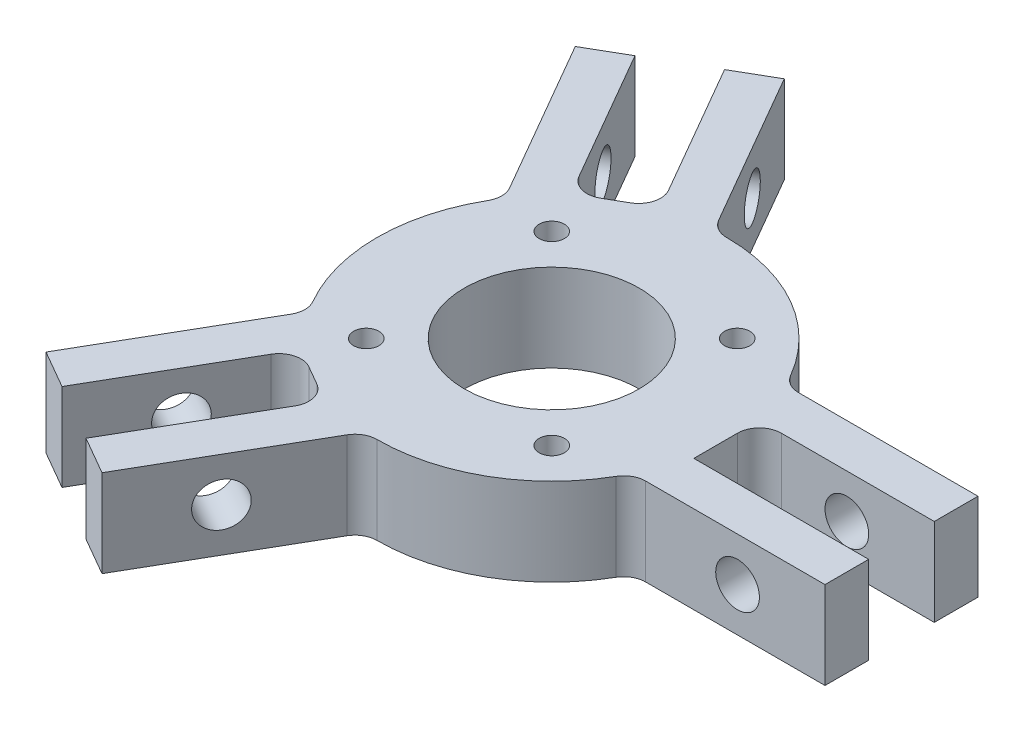
SolidWorks part; units mm, degrees
material "6061 Alloy"
ref_plane "Front Plane" through (0, 0, 0) normal (0, 0, 1) x (1, 0, 0)
ref_plane "Top Plane" through (0, 0, 0) normal (0, 1, 0) x (1, 0, 0)
ref_plane "Right Plane" through (0, 0, 0) normal (1, 0, 0) x (0, 0, -1)
sketch3d "Planning"
  line L0 (0, 0, 0) -> (38.1, 0, 0) construction
  line L1 (38.1, 0, 0) -> (355.6, -190.5, 0) construction
  line L2 (355.6, -190.5, 0) -> (355.6, -203.2, 0) construction
  line L3 (0, 0, 0) -> (-19.05, 0, 32.9956) construction
  line L4 (0, 0, 0) -> (-19.05, 0, -32.9956) construction
  line L5 (-19.05, 0, 32.9956) -> (-127, -190.5, 219.9705) construction
  line L6 (-127, -190.5, 219.9705) -> (-127, -203.2, 219.9705) construction
  line L7 (-19.05, 0, -32.9956) -> (-127, -190.5, -219.9705) construction
  line L8 (-127, -190.5, -219.9705) -> (-127, -203.2, -219.9705) construction
  line L9 (-19.05, 0, -32.9956) -> (-19.05, 0, 32.9956) construction
  line L10 (-127, -203.2, -219.9705) -> (-127, -203.2, 219.9705) construction
  line L11 (355.6, -203.2, 0) -> (-127, -203.2, 0) construction
  line L12 (0, 0, 0) -> (0, -203.2, 0) construction
  point P11 (-19.05, 0, 0)
  dimension "D1" = 38.1
  dimension "D2" = 12.7
  dimension "D3" = 203.2
  dimension "D4" = 482.6
  dimension "D5" = 127
  dimension "D6" = 120
sketch "Sketch1" plane through (0, 0, 0) normal (0, 1, 0) x (1, 0, 0)
  line L0 (0, 0) -> (25.4, 0) construction
  line L1 (25.4, 4.7625) -> (25.4, -4.7625)
  line L2 (25.4, -4.7625) -> (50.8, -4.7625)
  line L3 (50.8, -4.7625) -> (50.8, -11.1125)
  line L4 (25.4, 4.7625) -> (50.8, 4.7625)
  line L5 (13.4704, 13.4704) -> (-13.4704, -13.4704) construction
  line L6 (13.4704, -13.4704) -> (-13.4704, 13.4704) construction
  line L7 (50.8, 4.7625) -> (50.8, 11.1125)
  line L8 (0, 0) -> (-12.7, -21.997) construction
  line L9 (38.1, 4.7625) -> (38.1, -4.7625) construction
  line L10 (-35.0237, -38.4378) -> (-29.5244, -41.6128)
  line L11 (-29.5244, -41.6128) -> (-16.8244, -19.6158)
  line L12 (-16.8244, -19.6158) -> (-8.5756, -24.3783)
  line L13 (-8.5756, -24.3783) -> (-21.2756, -46.3753)
  line L14 (-21.2756, -46.3753) -> (-15.7763, -49.5503)
  line L15 (-15.7763, -49.5503) -> (-1.7964, -25.3364)
  line L16 (50.8, -11.1125) -> (22.8401, -11.1125)
  line L17 (-35.0237, -38.4378) -> (-21.0438, -14.2239)
  line L18 (0, 0) -> (-12.7, 21.997) construction
  line L19 (-15.7763, 49.5503) -> (-1.7964, 25.3364)
  line L20 (-21.2756, 46.3753) -> (-15.7763, 49.5503)
  line L21 (-8.5756, 24.3783) -> (-21.2756, 46.3753)
  line L22 (-16.8244, 19.6158) -> (-8.5756, 24.3783)
  line L23 (-29.5244, 41.6128) -> (-16.8244, 19.6158)
  line L24 (-35.0237, 38.4378) -> (-29.5244, 41.6128)
  line L25 (-35.0237, 38.4378) -> (-21.0438, 14.2239)
  line L26 (50.8, 11.1125) -> (22.8401, 11.1125)
  line L27 (0, 0) -> (-19.05, 32.9956) construction
  circle A0 centre (0, 0) radius 12.7
  circle A1 centre (-13.4704, 13.4704) radius 1.8288
  circle A2 centre (13.4704, 13.4704) radius 1.8288
  circle A3 centre (13.4704, -13.4704) radius 1.8288
  circle A4 centre (-13.4704, -13.4704) radius 1.8288
  arc A5 (-1.7964, -25.3364) -> (22.8401, -11.1125) centre (0, 0) ccw
  arc A6 (-1.7964, 25.3364) -> (22.8401, 11.1125) centre (0, 0) cw
  arc A7 (-21.0438, 14.2239) -> (-21.0438, -14.2239) centre (0, 0) ccw
  dimension "D3" = 25.4
  dimension "D5" = 3.6576
  dimension "D8" = 25.4
  dimension "D1" = 9.525
  dimension "D2" = 25.4
  dimension "D4" = 38.1
  dimension "D6" = 6.35
extrude "Boss-Extrude1" add sketch "Sketch1" along normal mid plane 12.7
hole_wizard "1/4 (0.25) Diameter Hole1" positions "3DSketch1" profile "Sketch4" hole size "1/4" standard "ANSI Inch"
sketch3d "3DSketch1"
  line L0 (25.4, -6.35, 4.7625) -> (50.8, 6.35, 4.7625) construction
  line L3 (25.4, -6.35, -4.7625) -> (50.8, 6.35, -4.7625) construction
  line L6 (-8.5756, -6.35, -24.3783) -> (-21.2756, 6.35, -46.3753) construction
  line L9 (-16.8244, -6.35, -19.6158) -> (-29.5244, 6.35, -41.6128) construction
  line L12 (-8.5756, -6.35, 24.3783) -> (-21.2756, 6.35, 46.3753) construction
  line L15 (-29.5244, 6.35, 41.6128) -> (-16.8244, -6.35, 19.6158) construction
  point P0 (38.1, 0, -4.7625)
  point P2 (-14.9256, 0, -35.3768)
  point P4 (-23.1744, 0, 30.6143)
  point P6 (-14.9256, 0, 35.3768)
  point P8 (-23.1744, 0, -30.6143)
  point P10 (38.1, 0, 4.7625)
sketch "Sketch4" plane through (38.1, 0, -4.7625) normal (1, 0, 0) x (0, -1, 0)
  line L0 (0, 0) -> (0, 6.35)
  line L1 (0, 6.35) -> (3.175, 6.35)
  line L2 (3.175, 6.35) -> (3.175, 0)
  line L5 (3.175, 0) -> (0, 0)
  line L11 (0, -6.35) -> (0, 107.95) construction
  dimension "Thru Hole Dia." = 6.35
  dimension "Thru Hole Depth" = 6.35
fillet "Fillet1" radius 3.175 11 edges at (-21.0438, 0, 14.2239) (-16.8244, 0, 19.6158) (-8.5756, 0, 24.3783) (-1.7964, 0, 25.3364) (22.8401, 0, 11.1125) (25.4, 0, -4.7625) (22.8401, 0, -11.1125) (-1.7964, 0, -25.3364) (-8.5756, 0, -24.3783) (-16.8244, 0, -19.6158) (-21.0438, 0, -14.2239)
